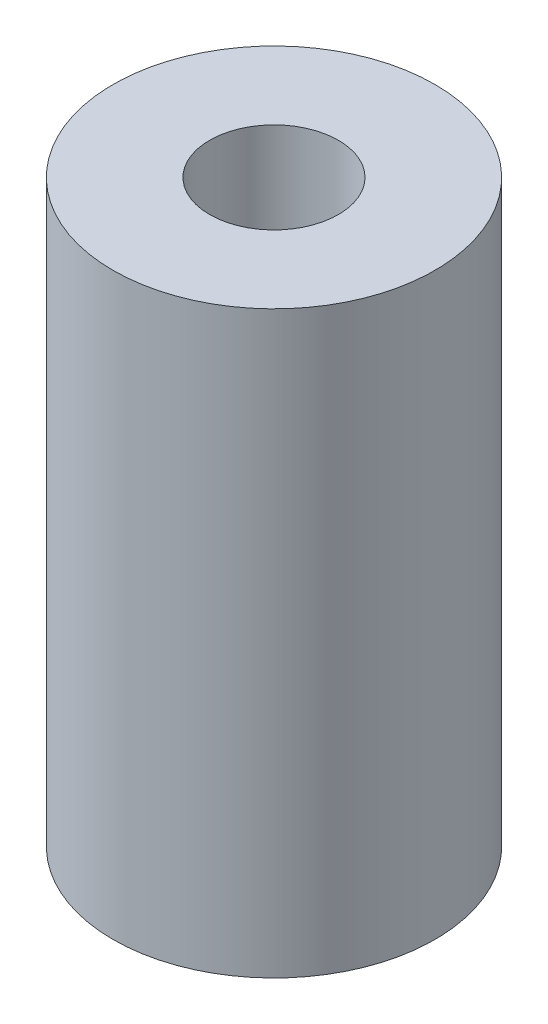
SolidWorks part; units mm, degrees
ref_plane "Front Plane" through (0, 0, 0) normal (0, 0, 1) x (1, 0, 0)
ref_plane "Top Plane" through (0, 0, 0) normal (0, 1, 0) x (1, 0, 0)
ref_plane "Right Plane" through (0, 0, 0) normal (1, 0, 0) x (0, 0, -1)
sketch "Sketch1" plane through (0, 0, 0) normal (0, 1, 0) x (1, 0, 0)
  circle A0 centre (0, 0) radius 2.5
  dimension "D1" = 5
extrude "Boss-Extrude1" add sketch "Sketch1" along normal blind 9
sketch "Sketch2" plane through (0, 9, 0) normal (0, 1, 0) x (1, 0, 0)
  circle A0 centre (0, 0) radius 1
  dimension "D1" = 2
extrude "Cut-Extrude1" cut sketch "Sketch2" against normal through all
